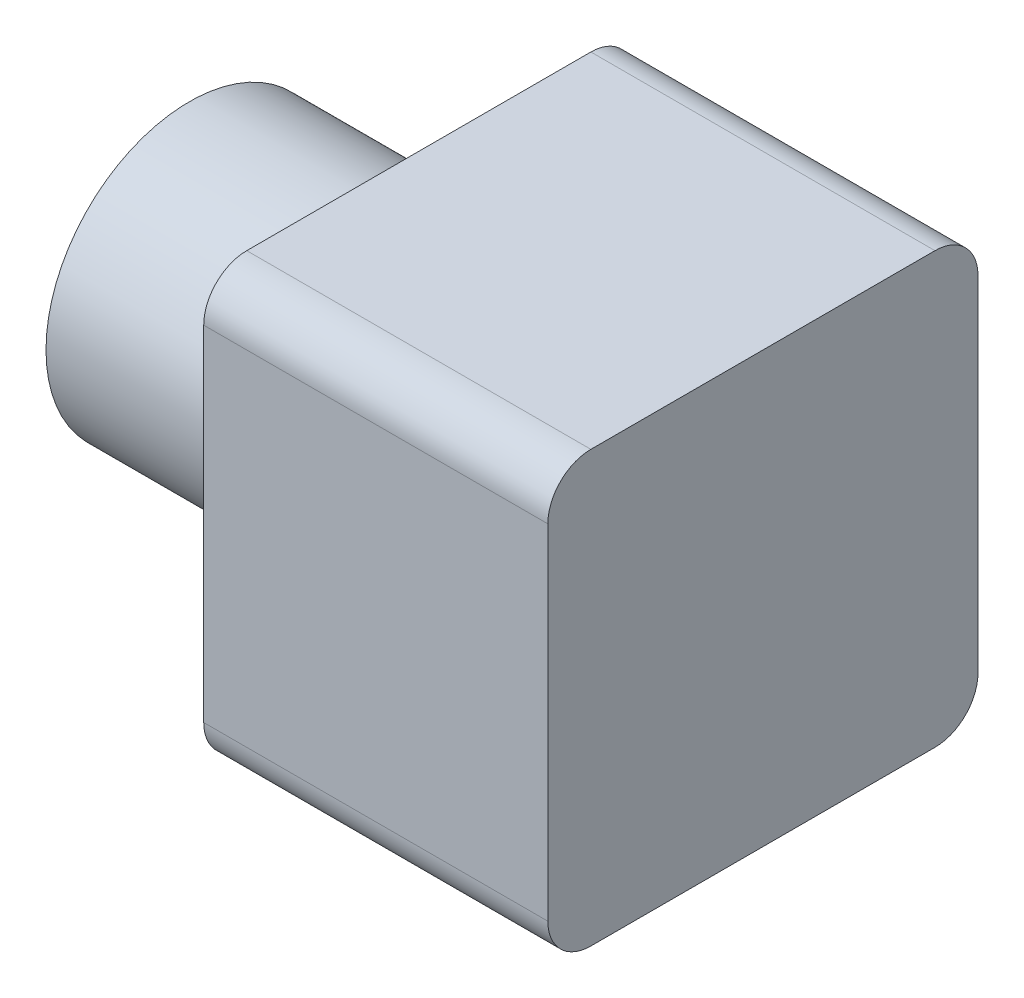
SolidWorks part; units mm, degrees
ref_plane "Front Plane" through (0, 0, 0) normal (0, 0, 1) x (1, 0, 0)
ref_plane "Top Plane" through (0, 0, 0) normal (0, 1, 0) x (1, 0, 0)
ref_plane "Right Plane" through (0, 0, 0) normal (1, 0, 0) x (0, 0, -1)
sketch "Sketch2" plane through (-36.1378, 0, 0) normal (-1, 0, 0) x (0, 0, 1)
  circle A0 centre (-25, -31.6006) radius 5
extrude "Boss-Extrude1" add sketch "Sketch2" along normal blind 8
sketch "Sketch3" plane through (-36.1378, 0, 0) normal (1, 0, 0) x (0, 0, -1)
  line L1 (17.5, -24.1006) -> (32.5, -24.1006)
  line L2 (17.5, -24.1006) -> (17.5, -39.1006)
  line L3 (17.5, -39.1006) -> (32.5, -39.1006)
  line L4 (32.5, -24.1006) -> (32.5, -39.1006)
  circle A0 centre (25, -31.6006) radius 5 construction
  dimension "D1" = 7.5
  dimension "D2" = 15
  dimension "D3" = 7.5
  dimension "D4" = 15
extrude "Boss-Extrude2" add sketch "Sketch3" along normal blind 12
sketch "Sketch4" plane through (-44.1378, 0, 0) normal (-1, 0, 0) x (0, 0, 1)
  circle A2 centre (-25, -31.6006) radius 4
  circle A3 centre (-25, -31.6006) radius 4
  dimension "D1" = 1
extrude "Cut-Extrude1" cut sketch "Sketch4" against normal blind 1
fillet "Fillet1" radius 1.5 4 edges at (-30.1378, -39.1006, -17.5) (-30.1378, -39.1006, -32.5) (-30.1378, -24.1006, -32.5) (-30.1378, -24.1006, -17.5)
